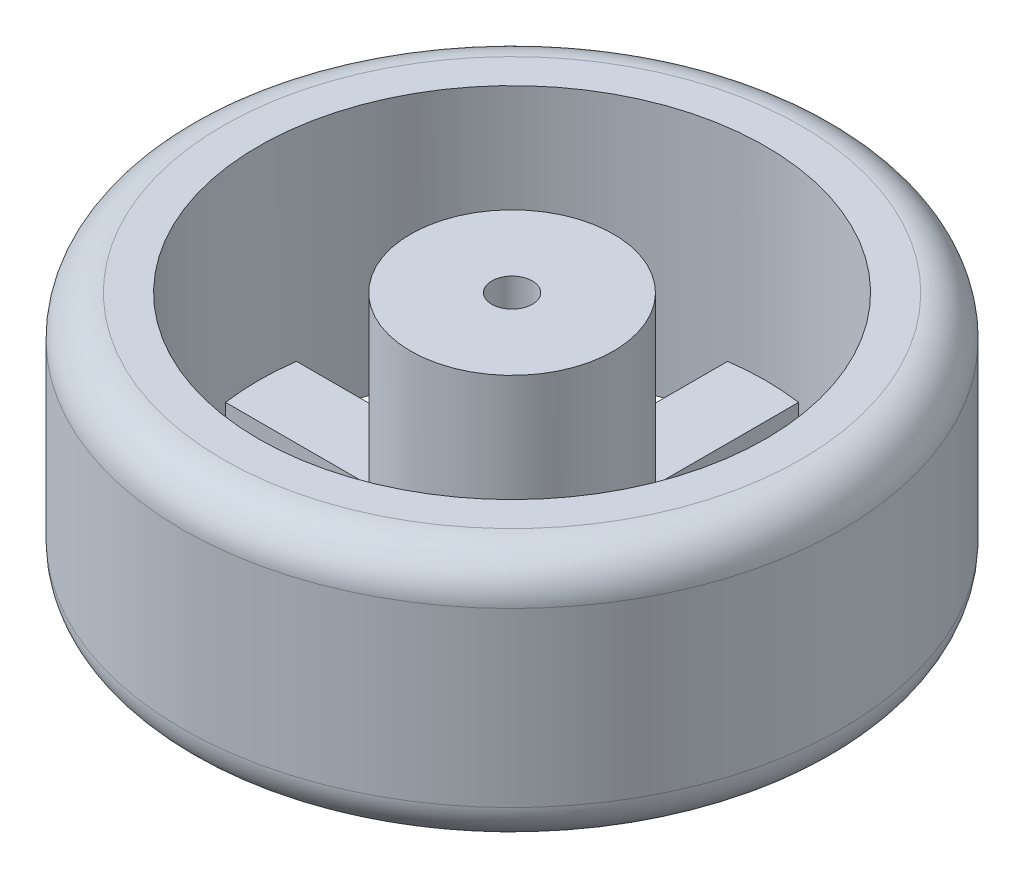
SolidWorks part; units mm, degrees
ref_plane "Front Plane" through (0, 0, 0) normal (0, 0, 1) x (1, 0, 0)
ref_plane "Top Plane" through (0, 0, 0) normal (0, 1, 0) x (1, 0, 0)
ref_plane "Right Plane" through (0, 0, 0) normal (1, 0, 0) x (0, 0, -1)
sketch "Sketch1" plane through (0, 0, 0) normal (0, 1, 0) x (1, 0, 0)
  circle A0 centre (0, 0) radius 32.5
  circle A1 centre (0, 0) radius 25
  dimension "D1" = 65
  dimension "D2" = 50
extrude "Boss-Extrude1" add sketch "Sketch1" along normal blind 25
sketch "Sketch2" plane through (0, 25, 0) normal (0, 1, 0) x (1, 0, 0)
  circle A0 centre (0, 0) radius 10
  point P3 (0, 0)
  dimension "D1" = 20
extrude "Boss-Extrude3" add sketch "Sketch2" against normal blind 25 separate body
sketch "Sketch4" plane through (0, 25, 0) normal (0, 1, 0) x (1, 0, 0)
  circle A0 centre (0, 0) radius 2
  dimension "D1" = 4
extrude "Cut-Extrude1" cut sketch "Sketch4" against normal blind 10
sketch "Sketch6" plane through (0, 0, 0) normal (0, -1, 0) x (-1, 0, 0)
  line L0 (0, 25) -> (0, -25) construction
  line L1 (3.5, 25) -> (3.5, -25)
  line L2 (-3.5, 25) -> (-3.5, -25)
  line L3 (25, 0) -> (-25, 0) construction
  line L4 (25, -3.5) -> (-25, -3.5)
  line L5 (25, 3.5) -> (-25, 3.5)
  circle A0 centre (0, 0) radius 25 construction
  arc A1 (3.5, 25) -> (-3.5, 25) centre (0, 25) ccw
  arc A2 (-3.5, -25) -> (3.5, -25) centre (0, -25) ccw
  arc A3 (25, -3.5) -> (25, 3.5) centre (25, 0) ccw
  arc A4 (-25, 3.5) -> (-25, -3.5) centre (-25, 0) ccw
  point P5 (0, 0)
  point P10 (0, 0)
  dimension "D1" = 7
  dimension "D2" = 50
  dimension "D3" = 7
  dimension "D4" = 50
extrude "Boss-Extrude5" add sketch "Sketch6" against normal blind 5
fillet "Fillet4" radius 4 2 edges at (0, 25, 32.5) (0, 0, 32.5)
